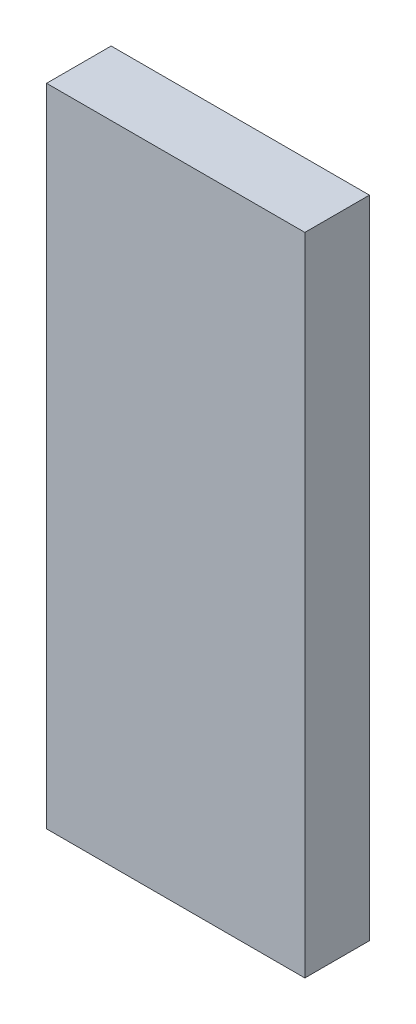
SolidWorks part; units mm, degrees
material "Акрил (Средняя-высокая ударопрочность)"
ref_plane "Front" through (0, 0, 0) normal (0, 0, 1) x (1, 0, 0)
ref_plane "Top" through (0, 0, 0) normal (0, 1, 0) x (1, 0, 0)
ref_plane "Right" through (0, 0, 0) normal (1, 0, 0) x (0, 0, -1)
sketch "Эскиз1" plane through (0, 0, 0) normal (0, 0, 1) x (1, 0, 0)
  line L1 (-10, 25) -> (10, 25)
  line L2 (-10, 25) -> (-10, -25)
  line L3 (-10, -25) -> (10, -25)
  line L4 (10, 25) -> (10, -25)
  line L5 (-10, 25) -> (10, -25) construction
  line L6 (-10, -25) -> (10, 25) construction
  point P0 (0, 0)
  dimension "D1" = 50
  dimension "D2" = 20
extrude "Бобышка-Вытянуть1" add sketch "Эскиз1" along normal blind 5
